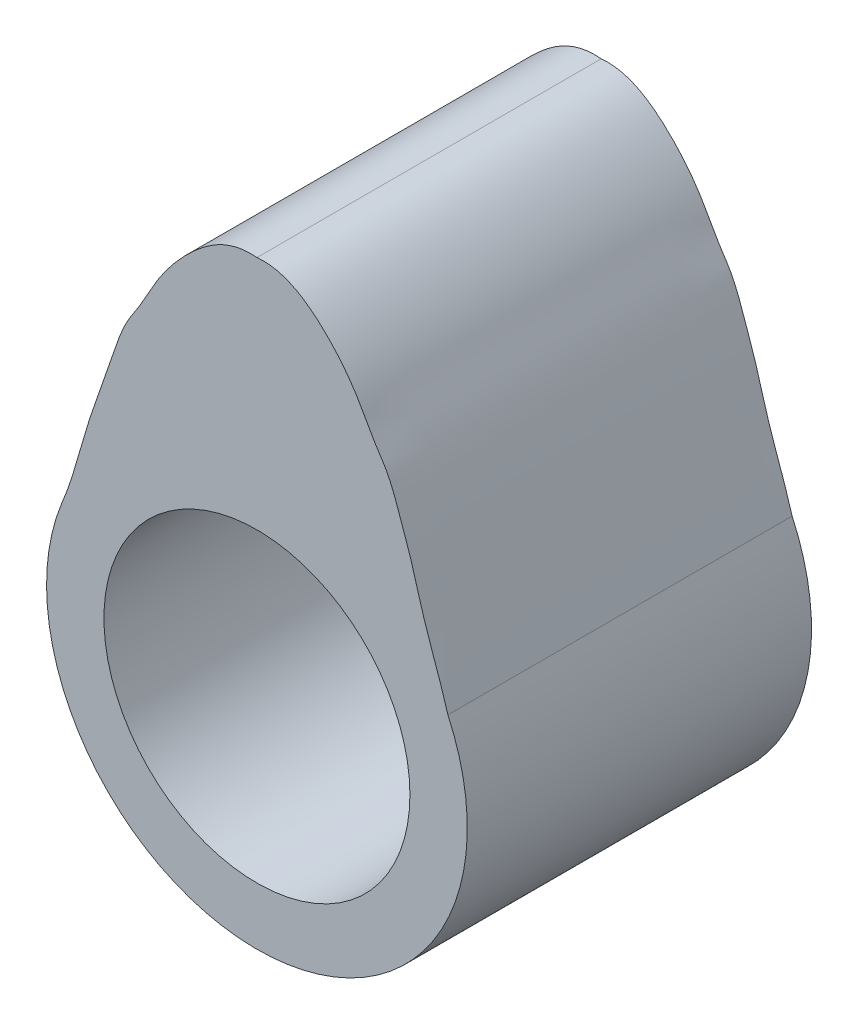
SolidWorks part; units mm, degrees
material "Легированная сталь"
ref_plane "Спереди" through (0, 0, 0) normal (0, 0, 1) x (1, 0, 0)
ref_plane "Сверху" through (0, 0, 0) normal (0, 1, 0) x (1, 0, 0)
ref_plane "Справа" through (0, 0, 0) normal (1, 0, 0) x (0, 0, -1)
sketch "Эскиз1" plane through (0, 0, 0) normal (0, 0, 1) x (1, 0, 0)
  circle A0 centre (0, 0) radius 8
  circle A1 centre (0, 0) radius 11
  spline S0 degree 3 poles (0, 20.3286) (1.3829, 20.4717) (3.3874, 19.141) (5.1492, 16.9374) (6.0198, 15.1896) (6.9473, 13.9011) (7.4819, 12.301) (8.1236, 10.5484) (8.7923, 7.9287) (9.5881, 5.9982) (9.9867, 4.6116) knots 0 0 0 0 0.197957 0.347933 0.427688 0.494985 0.588498 0.682567 0.7801 1 1 1 1
  spline S1 degree 3 poles (0, 20.3286) (-1.3828, 20.4717) (-3.3876, 19.141) (-5.1489, 16.9373) (-6.0203, 15.1898) (-6.9454, 13.9005) (-7.492, 12.3042) (-8.0892, 10.526) (-9.0891, 7.8082) (-9.574, 5.5761) (-10.2173, 4.0752) knots 0 0 0 0 0.192275 0.337945 0.415411 0.480776 0.571605 0.662973 0.759318 1 1 1 1
  dimension "D1" = 16
  dimension "D2" = 22
extrude "Бобышка-Вытянуть1" add sketch "Эскиз1" along normal blind 18 contours S0 S1 A1 | A1 S1 A0
